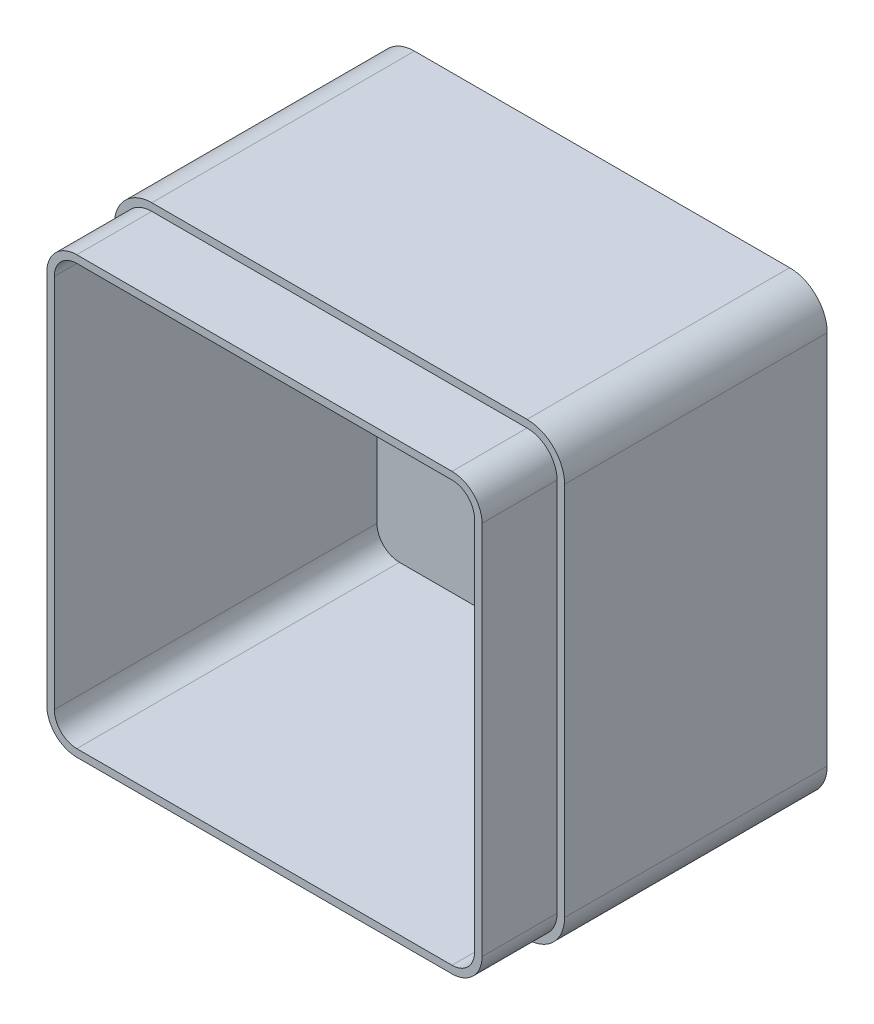
SolidWorks part; units mm, degrees
ref_plane "Front Plane" through (0, 0, 0) normal (0, 0, 1) x (1, 0, 0)
ref_plane "Top Plane" through (0, 0, 0) normal (0, 1, 0) x (1, 0, 0)
ref_plane "Right Plane" through (0, 0, 0) normal (1, 0, 0) x (0, 0, -1)
sketch "Sketch1" plane through (0, 0, 0) normal (0, 0, 1) x (1, 0, 0)
  line L1 (0, 0) -> (120, 0)
  line L2 (0, 0) -> (0, 120)
  line L3 (0, 120) -> (120, 120)
  line L4 (120, 0) -> (120, 120)
  dimension "D1" = 120
  dimension "D2" = 120
extrude "Boss-Extrude1" add sketch "Sketch1" along normal blind 90
fillet "Fillet1" radius 10 4 edges at (0, 0, 45) (120, 0, 45) (0, 120, 45) (120, 120, 45)
shell "Shell1" thickness 4
sketch "Sketch2" plane through (0, 0, 90) normal (0, 0, 1) x (1, 0, 0)
  line L0 (2, 110) -> (2, 10)
  line L1 (10, 2) -> (110, 2)
  line L2 (118, 10) -> (118, 110)
  line L3 (110, 118) -> (10, 118)
  line L4 (0, 110) -> (0, 10)
  line L5 (10, 0) -> (110, 0)
  line L6 (120, 10) -> (120, 110)
  line L7 (110, 120) -> (10, 120)
  line L8 (0, 110) -> (0, 10)
  line L9 (10, 0) -> (110, 0)
  line L10 (120, 10) -> (120, 110)
  line L11 (110, 120) -> (10, 120)
  arc A0 (2, 10) -> (10, 2) centre (10, 10) ccw
  arc A1 (110, 2) -> (118, 10) centre (110, 10) ccw
  arc A2 (118, 110) -> (110, 118) centre (110, 110) ccw
  arc A3 (10, 118) -> (2, 110) centre (10, 110) ccw
  arc A4 (0, 10) -> (10, 0) centre (10, 10) ccw
  arc A5 (110, 0) -> (120, 10) centre (110, 10) ccw
  arc A6 (120, 110) -> (110, 120) centre (110, 110) ccw
  arc A7 (10, 120) -> (0, 110) centre (10, 110) ccw
  arc A8 (0, 10) -> (10, 0) centre (10, 10) ccw
  arc A9 (110, 0) -> (120, 10) centre (110, 10) ccw
  arc A10 (120, 110) -> (110, 120) centre (110, 110) ccw
  arc A11 (10, 120) -> (0, 110) centre (10, 110) ccw
  dimension "D1" = 0
  dimension "D2" = 2
extrude "Cut-Extrude1" cut sketch "Sketch2" against normal blind 20 contours L11 A11 L8 A8 L9 A9 L10 A10
